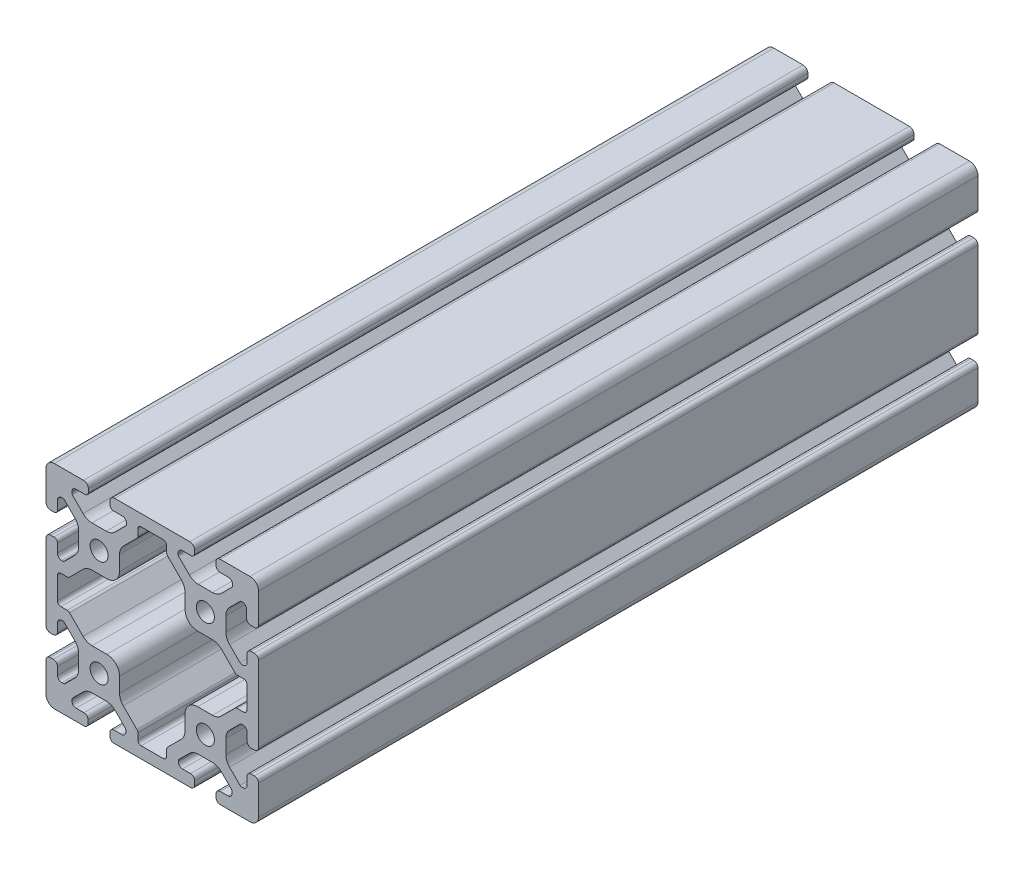
SolidWorks part; units mm, degrees
material "6061 Alloy"
ref_plane "Front Plane" through (0, 0, 0) normal (0, 0, 1) x (1, 0, 0)
ref_plane "Top Plane" through (0, 0, 0) normal (0, 1, 0) x (1, 0, 0)
ref_plane "Right Plane" through (0, 0, 0) normal (1, 0, 0) x (0, 0, -1)
sketch "Sketch1" plane through (0, 0, 0) normal (0, 0, 1) x (1, 0, 0)
  line L0 (0, -40) -> (0, 40) construction
  line L1 (0, 0) -> (-43.5804, 43.5804) construction
  line L2 (-20, 20) -> (-47.7323, 20) construction
  line L3 (-20, 20) -> (3.796, 43.796) construction
  line L4 (-20, 20) -> (-20, 43.5758) construction
  line L5 (-20, -27.7) -> (-20, -47.5576) construction
  line L7 (-36.8718, 24) -> (-28.8718, 24) construction
  line L8 (-36.8718, 24) -> (-36.8718, 16) construction
  line L9 (-36.8718, 16) -> (-28.8718, 16) construction
  line L10 (-28.8718, 24) -> (-28.8718, 16) construction
  line L11 (-36.8718, 24) -> (-28.8718, 16) construction
  line L12 (-36.8718, 16) -> (-28.8718, 24) construction
  line L131 (29.0912, 26.0365) -> (33.0827, 30.028)
  line L132 (27.7, 17.3222) -> (27.7, 22.6778)
  line L133 (29.0912, 13.9635) -> (33.0827, 9.972)
  line L134 (33.6201, 9.7494) -> (34.11, 9.7494)
  line L135 (35.68, 11.3194) -> (35.68, 14.2221)
  line L136 (37.25, 15.7921) -> (38.43, 15.7921)
  line L137 (40, 14.2221) -> (40, 7.0214)
  line L138 (40, 7.0214) -> (40, -7.0214)
  line L139 (40, -7.0214) -> (40, -14.2221)
  line L140 (38.43, -15.7921) -> (37.25, -15.7921)
  line L141 (35.68, -14.2221) -> (35.68, -11.3194)
  line L142 (33.6201, -9.7494) -> (34.11, -9.7494)
  line L143 (29.0912, -13.9635) -> (33.0827, -9.972)
  line L144 (27.7, -22.6778) -> (27.7, -17.3222)
  line L145 (29.0912, -26.0365) -> (33.0827, -30.028)
  line L146 (33.6201, -30.2506) -> (34.11, -30.2506)
  line L147 (35.68, -28.6806) -> (35.68, -25.7779)
  line L148 (37.25, -24.2079) -> (38.43, -24.2079)
  line L149 (40, -25.7779) -> (40, -33.0259)
  line L150 (40, -33.0259) -> (40, -36.83)
  line L151 (36.83, -40) -> (32.9998, -40)
  line L152 (32.9998, -40) -> (25.5696, -40)
  line L153 (23.9996, -38.43) -> (23.9996, -37.25)
  line L154 (25.5696, -35.68) -> (28.4723, -35.68)
  line L155 (30.0413, -34.0552) -> (30.0171, -33.3605)
  line L156 (29.7949, -32.8496) -> (26.0365, -29.0912)
  line L157 (17.3222, -27.7) -> (22.6778, -27.7)
  line L158 (10.035, -33.0197) -> (13.9635, -29.0912)
  line L159 (9.8124, -33.8926) -> (9.8124, -33.5571)
  line L160 (11.3824, -35.4626) -> (14.4246, -35.4626)
  line L161 (15.9946, -37.0326) -> (15.9946, -38.43)
  line L162 (14.4246, -40) -> (6.9987, -40)
  line L163 (6.9987, -40) -> (-6.9987, -40)
  line L164 (-6.9987, -40) -> (-14.4292, -40)
  line L165 (-15.9992, -38.43) -> (-15.9992, -37.25)
  line L166 (-14.4292, -35.68) -> (-11.5265, -35.68)
  line L167 (-9.9574, -34.0552) -> (-9.9816, -33.3618)
  line L168 (-10.2038, -32.8509) -> (-13.9635, -29.0912)
  line L169 (-22.6778, -27.7) -> (-17.3222, -27.7)
  line L170 (-30.028, -33.0827) -> (-26.0365, -29.0912)
  line L171 (-30.2506, -34.11) -> (-30.2506, -33.6201)
  line L172 (-28.6806, -35.68) -> (-25.7231, -35.68)
  line L173 (-24.1531, -37.25) -> (-24.1531, -38.43)
  line L174 (-25.7231, -40) -> (-33, -40)
  line L175 (-33, -40) -> (-36.83, -40)
  line L176 (-40, -36.83) -> (-40, -33.0191)
  line L177 (-40, -33.0191) -> (-40, -25.591)
  line L178 (-38.43, -24.021) -> (-37.25, -24.021)
  line L179 (-35.68, -28.4937) -> (-35.68, -25.591)
  line L180 (-34.0552, -30.0627) -> (-33.3827, -30.0392)
  line L181 (-32.8718, -29.8171) -> (-29.0912, -26.0365)
  line L182 (-27.7, -22.6778) -> (-27.7, -17.3222)
  line L183 (-29.0912, -13.9635) -> (-33.0827, -9.972)
  line L184 (-34.11, -9.7494) -> (-33.6201, -9.7494)
  line L185 (-35.68, -11.3194) -> (-35.68, -14.4473)
  line L186 (-38.43, -16.0173) -> (-37.25, -16.0173)
  line L187 (-40, -14.4473) -> (-40, -7.0169)
  line L188 (-40, -7.0169) -> (-40, 7.0169)
  line L189 (-40, 7.0169) -> (-40, 14.1348)
  line L190 (-38.1948, 15.94) -> (-36.9772, 15.94)
  line L191 (-35.68, 11.3194) -> (-35.68, 14.6428)
  line L192 (-34.11, 9.7494) -> (-33.6201, 9.7494)
  line L193 (-33.0827, 9.972) -> (-29.0912, 13.9635)
  line L194 (-27.7, 17.3222) -> (-27.7, 22.6778)
  line L195 (-29.0912, 26.0365) -> (-33.0827, 30.028)
  line L196 (-34.11, 30.2506) -> (-33.6201, 30.2506)
  line L197 (-35.68, 28.6806) -> (-35.68, 25.3572)
  line L198 (-38.1948, 24.06) -> (-36.9772, 24.06)
  line L199 (-40, 25.8652) -> (-40, 33.3181)
  line L200 (-40, 33.3181) -> (-40, 36.83)
  line L201 (-36.83, 40) -> (-33.0314, 40)
  line L202 (-33.0314, 40) -> (-25.8652, 40)
  line L203 (-24.06, 36.9772) -> (-24.06, 38.1948)
  line L204 (-25.3572, 35.68) -> (-28.7018, 35.68)
  line L205 (-30.285, 33.6069) -> (-30.285, 34.0968)
  line L206 (-30.0961, 33.1508) -> (-26.0365, 29.0912)
  line L207 (-22.6778, 27.7) -> (-17.3222, 27.7)
  line L208 (-13.9635, 29.0912) -> (-9.9039, 33.1508)
  line L209 (-9.715, 33.6069) -> (-9.715, 34.0968)
  line L210 (-14.6428, 35.68) -> (-11.2982, 35.68)
  line L211 (-15.94, 36.9772) -> (-15.94, 38.1948)
  line L212 (-14.1348, 40) -> (-6.9844, 40)
  line L213 (-6.9844, 40) -> (6.9844, 40)
  line L214 (6.9844, 40) -> (14.1348, 40)
  line L215 (15.94, 36.9772) -> (15.94, 38.1948)
  line L216 (14.6428, 35.68) -> (11.2982, 35.68)
  line L217 (9.715, 33.6069) -> (9.715, 34.0968)
  line L218 (9.9039, 33.1508) -> (13.9635, 29.0912)
  line L219 (17.3222, 27.7) -> (22.6778, 27.7)
  line L220 (26.0365, 29.0912) -> (30.028, 33.0827)
  line L221 (30.2506, 33.6201) -> (30.2506, 34.11)
  line L222 (25.5409, 35.679) -> (28.6258, 35.679)
  line L223 (23.9709, 37.249) -> (23.9709, 38.43)
  line L224 (25.5409, 40) -> (36.83, 40)
  line L226 (40, 36.83) -> (40, 32.9339)
  line L227 (40, 32.9339) -> (40, 25.7779)
  line L228 (38.43, 24.2079) -> (37.0956, 24.2079)
  line L229 (35.5256, 25.7779) -> (35.5256, 28.6806)
  line L230 (33.6201, 30.2506) -> (33.9556, 30.2506)
  line L231 (17.07, 12.32) -> (22.6578, 12.32)
  line L232 (26.0165, 10.9288) -> (31.1439, 5.8014)
  line L233 (32.0419, 5.4294) -> (34.41, 5.4294)
  line L234 (35.68, -4.1594) -> (35.68, 4.1594)
  line L235 (32.0419, -5.4294) -> (34.41, -5.4294)
  line L236 (26.0165, -10.9288) -> (31.1439, -5.8014)
  line L237 (17.07, -12.32) -> (22.6578, -12.32)
  line L238 (12.32, -22.6578) -> (12.32, -17.07)
  line L239 (5.8014, -31.1439) -> (10.9288, -26.0165)
  line L240 (5.4294, -34.41) -> (5.4294, -32.0419)
  line L241 (-4.1594, -35.68) -> (4.1594, -35.68)
  line L242 (-5.4294, -34.41) -> (-5.4294, -32.0419)
  line L243 (-5.8014, -31.1439) -> (-10.9288, -26.0165)
  line L244 (-12.32, -22.6578) -> (-12.32, -17.07)
  line L245 (-22.6578, -12.32) -> (-17.07, -12.32)
  line L246 (-26.0165, -10.9288) -> (-31.1439, -5.8014)
  line L247 (-34.41, -5.4294) -> (-32.0419, -5.4294)
  line L248 (-35.68, -4.1594) -> (-35.68, 4.1594)
  line L249 (-34.41, 5.4294) -> (-32.0419, 5.4294)
  line L250 (-31.1439, 5.8014) -> (-26.0165, 10.9288)
  line L251 (-22.6578, 12.32) -> (-17.07, 12.32)
  line L252 (-12.32, 17.07) -> (-12.32, 22.6578)
  line L253 (-10.9288, 26.0165) -> (-5.8014, 31.1439)
  line L254 (-5.4294, 32.0419) -> (-5.4294, 34.41)
  line L255 (-4.1594, 35.68) -> (4.1594, 35.68)
  line L256 (5.4294, 32.0419) -> (5.4294, 34.41)
  line L257 (5.8014, 31.1439) -> (10.9288, 26.0165)
  line L258 (12.32, 17.07) -> (12.32, 22.6578)
  line L260 (-40, 0) -> (40, 0) construction
  circle A0 centre (-32.8718, 20) radius 4 construction
  circle A116 centre (-20, 20) radius 3.4
  circle A117 centre (20, 20) radius 3.4
  circle A118 centre (20, -20) radius 3.4
  circle A119 centre (-20, -20) radius 3.4
  arc A120 (29.0912, 26.0365) -> (27.7, 22.6778) centre (32.45, 22.6778) ccw
  arc A121 (27.7, 17.3222) -> (29.0912, 13.9635) centre (32.45, 17.3222) ccw
  arc A122 (33.0827, 9.972) -> (33.6201, 9.7494) centre (33.6201, 10.5094) ccw
  arc A123 (34.11, 9.7494) -> (35.68, 11.3194) centre (34.11, 11.3194) ccw
  arc A124 (37.25, 15.7921) -> (35.68, 14.2221) centre (37.25, 14.2221) ccw
  arc A125 (40, 14.2221) -> (38.43, 15.7921) centre (38.43, 14.2221) ccw
  arc A126 (38.43, -15.7921) -> (40, -14.2221) centre (38.43, -14.2221) ccw
  arc A127 (35.68, -14.2221) -> (37.25, -15.7921) centre (37.25, -14.2221) ccw
  arc A128 (35.68, -11.3194) -> (34.11, -9.7494) centre (34.11, -11.3194) ccw
  arc A129 (33.6201, -9.7494) -> (33.0827, -9.972) centre (33.6201, -10.5094) ccw
  arc A130 (29.0912, -13.9635) -> (27.7, -17.3222) centre (32.45, -17.3222) ccw
  arc A131 (27.7, -22.6778) -> (29.0912, -26.0365) centre (32.45, -22.6778) ccw
  arc A132 (33.0827, -30.028) -> (33.6201, -30.2506) centre (33.6201, -29.4906) ccw
  arc A133 (34.11, -30.2506) -> (35.68, -28.6806) centre (34.11, -28.6806) ccw
  arc A134 (37.25, -24.2079) -> (35.68, -25.7779) centre (37.25, -25.7779) ccw
  arc A135 (40, -25.7779) -> (38.43, -24.2079) centre (38.43, -25.7779) ccw
  arc A136 (36.83, -40) -> (40, -36.83) centre (36.83, -36.83) ccw
  arc A137 (23.9996, -38.43) -> (25.5696, -40) centre (25.5696, -38.43) ccw
  arc A138 (25.5696, -35.68) -> (23.9996, -37.25) centre (25.5696, -37.25) ccw
  arc A139 (28.4723, -35.68) -> (30.0413, -34.0552) centre (28.4723, -34.11) ccw
  arc A140 (30.0171, -33.3605) -> (29.7949, -32.8496) centre (29.2575, -33.387) ccw
  arc A141 (26.0365, -29.0912) -> (22.6778, -27.7) centre (22.6778, -32.45) ccw
  arc A142 (17.3222, -27.7) -> (13.9635, -29.0912) centre (17.3222, -32.45) ccw
  arc A143 (10.035, -33.0197) -> (9.8124, -33.5571) centre (10.5724, -33.5571) ccw
  arc A144 (9.8124, -33.8926) -> (11.3824, -35.4626) centre (11.3824, -33.8926) ccw
  arc A145 (15.9946, -37.0326) -> (14.4246, -35.4626) centre (14.4246, -37.0326) ccw
  arc A146 (14.4246, -40) -> (15.9946, -38.43) centre (14.4246, -38.43) ccw
  arc A147 (-15.9992, -38.43) -> (-14.4292, -40) centre (-14.4292, -38.43) ccw
  arc A148 (-14.4292, -35.68) -> (-15.9992, -37.25) centre (-14.4292, -37.25) ccw
  arc A149 (-11.5265, -35.68) -> (-9.9574, -34.0552) centre (-11.5265, -34.11) ccw
  arc A150 (-9.9816, -33.3618) -> (-10.2038, -32.8509) centre (-10.7412, -33.3883) ccw
  arc A151 (-13.9635, -29.0912) -> (-17.3222, -27.7) centre (-17.3222, -32.45) ccw
  arc A152 (-22.6778, -27.7) -> (-26.0365, -29.0912) centre (-22.6778, -32.45) ccw
  arc A153 (-30.028, -33.0827) -> (-30.2506, -33.6201) centre (-29.4906, -33.6201) ccw
  arc A154 (-30.2506, -34.11) -> (-28.6806, -35.68) centre (-28.6806, -34.11) ccw
  arc A155 (-24.1531, -37.25) -> (-25.7231, -35.68) centre (-25.7231, -37.25) ccw
  arc A156 (-25.7231, -40) -> (-24.1531, -38.43) centre (-25.7231, -38.43) ccw
  arc A157 (-40, -36.83) -> (-36.83, -40) centre (-36.83, -36.83) ccw
  arc A158 (-38.43, -24.021) -> (-40, -25.591) centre (-38.43, -25.591) ccw
  arc A159 (-35.68, -25.591) -> (-37.25, -24.021) centre (-37.25, -25.591) ccw
  arc A160 (-35.68, -28.4937) -> (-34.0552, -30.0627) centre (-34.11, -28.4937) ccw
  arc A161 (-33.3827, -30.0392) -> (-32.8718, -29.8171) centre (-33.4092, -29.2797) ccw
  arc A162 (-29.0912, -26.0365) -> (-27.7, -22.6778) centre (-32.45, -22.6778) ccw
  arc A163 (-27.7, -17.3222) -> (-29.0912, -13.9635) centre (-32.45, -17.3222) ccw
  arc A164 (-33.0827, -9.972) -> (-33.6201, -9.7494) centre (-33.6201, -10.5094) ccw
  arc A165 (-34.11, -9.7494) -> (-35.68, -11.3194) centre (-34.11, -11.3194) ccw
  arc A166 (-37.25, -16.0173) -> (-35.68, -14.4473) centre (-37.25, -14.4473) ccw
  arc A167 (-40, -14.4473) -> (-38.43, -16.0173) centre (-38.43, -14.4473) ccw
  arc A168 (-38.1948, 15.94) -> (-40, 14.1348) centre (-38.1948, 14.1348) ccw
  arc A169 (-35.68, 14.6428) -> (-36.9772, 15.94) centre (-36.9772, 14.6428) ccw
  arc A170 (-35.68, 11.3194) -> (-34.11, 9.7494) centre (-34.11, 11.3194) ccw
  arc A171 (-33.6201, 9.7494) -> (-33.0827, 9.972) centre (-33.6201, 10.5094) ccw
  arc A172 (-29.0912, 13.9635) -> (-27.7, 17.3222) centre (-32.45, 17.3222) ccw
  arc A173 (-27.7, 22.6778) -> (-29.0912, 26.0365) centre (-32.45, 22.6778) ccw
  arc A174 (-33.0827, 30.028) -> (-33.6201, 30.2506) centre (-33.6201, 29.4906) ccw
  arc A175 (-34.11, 30.2506) -> (-35.68, 28.6806) centre (-34.11, 28.6806) ccw
  arc A176 (-36.9772, 24.06) -> (-35.68, 25.3572) centre (-36.9772, 25.3572) ccw
  arc A177 (-40, 25.8652) -> (-38.1948, 24.06) centre (-38.1948, 25.8652) ccw
  arc A178 (-36.83, 40) -> (-40, 36.83) centre (-36.83, 36.83) ccw
  arc A179 (-24.06, 38.1948) -> (-25.8652, 40) centre (-25.8652, 38.1948) ccw
  arc A180 (-25.3572, 35.68) -> (-24.06, 36.9772) centre (-25.3572, 36.9772) ccw
  arc A181 (-28.7018, 35.68) -> (-30.285, 34.0968) centre (-28.7018, 34.0968) ccw
  arc A182 (-30.285, 33.6069) -> (-30.0961, 33.1508) centre (-29.6399, 33.6069) ccw
  arc A183 (-26.0365, 29.0912) -> (-22.6778, 27.7) centre (-22.6778, 32.45) ccw
  arc A184 (-17.3222, 27.7) -> (-13.9635, 29.0912) centre (-17.3222, 32.45) ccw
  arc A185 (-9.9039, 33.1508) -> (-9.715, 33.6069) centre (-10.3601, 33.6069) ccw
  arc A186 (-9.715, 34.0968) -> (-11.2982, 35.68) centre (-11.2982, 34.0968) ccw
  arc A187 (-15.94, 36.9772) -> (-14.6428, 35.68) centre (-14.6428, 36.9772) ccw
  arc A188 (-14.1348, 40) -> (-15.94, 38.1948) centre (-14.1348, 38.1948) ccw
  arc A189 (15.94, 38.1948) -> (14.1348, 40) centre (14.1348, 38.1948) ccw
  arc A190 (14.6428, 35.68) -> (15.94, 36.9772) centre (14.6428, 36.9772) ccw
  arc A191 (11.2982, 35.68) -> (9.715, 34.0968) centre (11.2982, 34.0968) ccw
  arc A192 (9.715, 33.6069) -> (9.9039, 33.1508) centre (10.3601, 33.6069) ccw
  arc A193 (13.9635, 29.0912) -> (17.3222, 27.7) centre (17.3222, 32.45) ccw
  arc A194 (22.6778, 27.7) -> (26.0365, 29.0912) centre (22.6778, 32.45) ccw
  arc A195 (30.028, 33.0827) -> (30.2506, 33.6201) centre (29.4906, 33.6201) ccw
  arc A196 (30.2506, 34.11) -> (28.6258, 35.679) centre (28.6806, 34.11) ccw
  arc A197 (23.9709, 37.249) -> (25.5409, 35.679) centre (25.5409, 37.249) ccw
  arc A198 (25.5409, 40) -> (23.9709, 38.43) centre (25.5409, 38.43) ccw
  arc A199 (40, 36.83) -> (36.83, 40) centre (36.83, 36.83) ccw
  arc A200 (38.43, 24.2079) -> (40, 25.7779) centre (38.43, 25.7779) ccw
  arc A201 (35.5256, 25.7779) -> (37.0956, 24.2079) centre (37.0956, 25.7779) ccw
  arc A202 (35.5256, 28.6806) -> (33.9556, 30.2506) centre (33.9556, 28.6806) ccw
  arc A203 (33.6201, 30.2506) -> (33.0827, 30.028) centre (33.6201, 29.4906) ccw
  arc A204 (26.0165, 10.9288) -> (22.6578, 12.32) centre (22.6578, 7.57) ccw
  arc A205 (31.1439, 5.8014) -> (32.0419, 5.4294) centre (32.0419, 6.6994) ccw
  arc A206 (35.68, 4.1594) -> (34.41, 5.4294) centre (34.41, 4.1594) ccw
  arc A207 (34.41, -5.4294) -> (35.68, -4.1594) centre (34.41, -4.1594) ccw
  arc A208 (32.0419, -5.4294) -> (31.1439, -5.8014) centre (32.0419, -6.6994) ccw
  arc A209 (22.6578, -12.32) -> (26.0165, -10.9288) centre (22.6578, -7.57) ccw
  arc A210 (17.07, -12.32) -> (12.32, -17.07) centre (17.07, -17.07) ccw
  arc A211 (10.9288, -26.0165) -> (12.32, -22.6578) centre (7.57, -22.6578) ccw
  arc A212 (5.8014, -31.1439) -> (5.4294, -32.0419) centre (6.6994, -32.0419) ccw
  arc A213 (4.1594, -35.68) -> (5.4294, -34.41) centre (4.1594, -34.41) ccw
  arc A214 (-5.4294, -34.41) -> (-4.1594, -35.68) centre (-4.1594, -34.41) ccw
  arc A215 (-5.4294, -32.0419) -> (-5.8014, -31.1439) centre (-6.6994, -32.0419) ccw
  arc A216 (-12.32, -22.6578) -> (-10.9288, -26.0165) centre (-7.57, -22.6578) ccw
  arc A217 (-12.32, -17.07) -> (-17.07, -12.32) centre (-17.07, -17.07) ccw
  arc A218 (-26.0165, -10.9288) -> (-22.6578, -12.32) centre (-22.6578, -7.57) ccw
  arc A219 (-31.1439, -5.8014) -> (-32.0419, -5.4294) centre (-32.0419, -6.6994) ccw
  arc A220 (-35.68, -4.1594) -> (-34.41, -5.4294) centre (-34.41, -4.1594) ccw
  arc A221 (-34.41, 5.4294) -> (-35.68, 4.1594) centre (-34.41, 4.1594) ccw
  arc A222 (-32.0419, 5.4294) -> (-31.1439, 5.8014) centre (-32.0419, 6.6994) ccw
  arc A223 (-22.6578, 12.32) -> (-26.0165, 10.9288) centre (-22.6578, 7.57) ccw
  arc A224 (-17.07, 12.32) -> (-12.32, 17.07) centre (-17.07, 17.07) ccw
  arc A225 (-10.9288, 26.0165) -> (-12.32, 22.6578) centre (-7.57, 22.6578) ccw
  arc A226 (-5.8014, 31.1439) -> (-5.4294, 32.0419) centre (-6.6994, 32.0419) ccw
  arc A227 (-4.1594, 35.68) -> (-5.4294, 34.41) centre (-4.1594, 34.41) ccw
  arc A228 (5.4294, 34.41) -> (4.1594, 35.68) centre (4.1594, 34.41) ccw
  arc A229 (5.4294, 32.0419) -> (5.8014, 31.1439) centre (6.6994, 32.0419) ccw
  arc A230 (12.32, 22.6578) -> (10.9288, 26.0165) centre (7.57, 22.6578) ccw
  arc A231 (12.32, 17.07) -> (17.07, 12.32) centre (17.07, 17.07) ccw
  point P9 (-32.8718, 20)
  dimension "D8" = 6.8
  dimension "D1" = 80
  dimension "D2" = 40
  dimension "D3" = 20
  dimension "D4" = 20.57
  dimension "D5" = 4.32
  dimension "D6" = 4.32
  dimension "D7" = 8.12
  dimension "D9" = 4.32
  dimension "D10" = 12.3
  dimension "D11" = 8
  dimension "D12" = 8
extrude "Extrude1" add sketch "Sketch1" against normal blind 270.85
